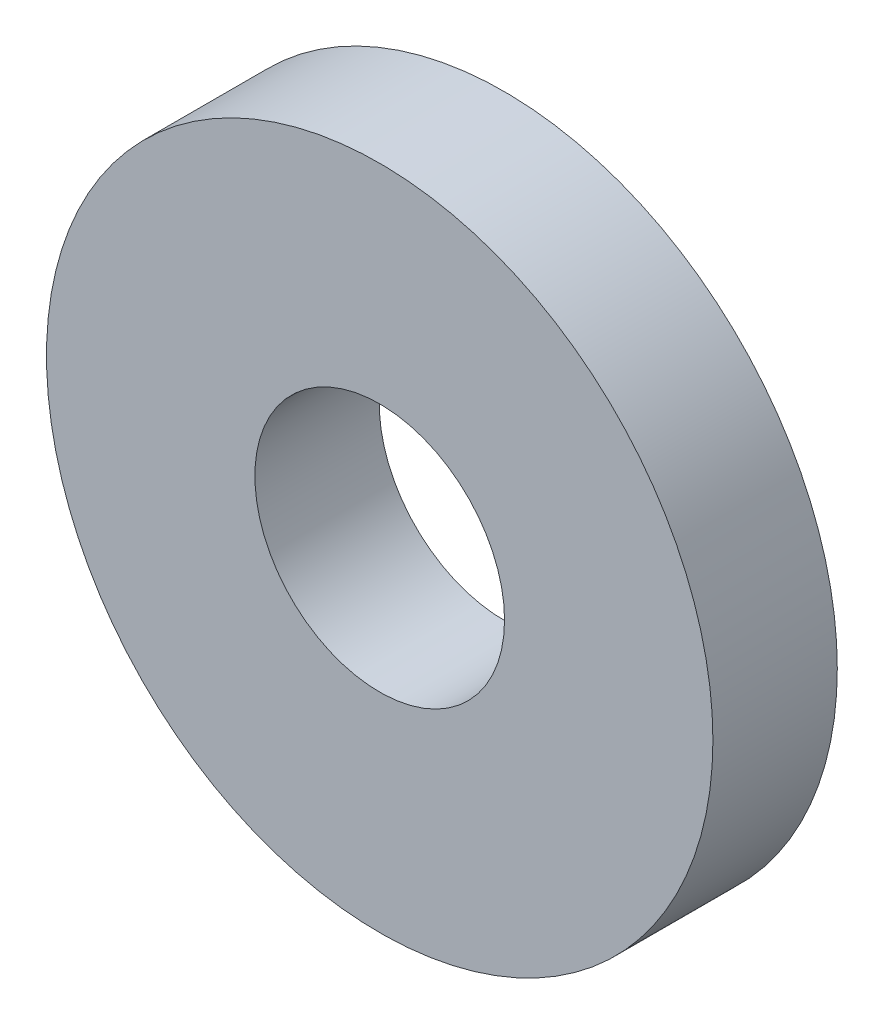
SolidWorks part; units mm, degrees
ref_plane "Front Plane" through (0, 0, 0) normal (0, 0, 1) x (1, 0, 0)
ref_plane "Top Plane" through (0, 0, 0) normal (0, 1, 0) x (1, 0, 0)
ref_plane "Right Plane" through (0, 0, 0) normal (1, 0, 0) x (0, 0, -1)
sketch "Sketch1" plane through (0, 0, 0) normal (1, 0, 0) x (0, 0, -1)
  line L0 (0, -3.5687) -> (0, 3.5687) construction
  line L1 (0, -9.525) -> (0, 9.525) construction
  line L2 (-1.778, 9.525) -> (1.778, 9.525)
  point P4 (0, 0)
  point P8 (0, 0)
  point P10 (0, 9.525)
  dimension "Thickness" = 3.556
sketch "Sketch2" plane through (0, 0, 0) normal (0, 0, 1) x (1, 0, 0)
  line L1 (0, -3.5687) -> (0, 3.5687) construction
  circle A2 centre (0, 0) radius 3.5687
  circle A3 centre (0, 0) radius 9.525
  point P3 (0, 0)
  dimension "D1" = 7.1374
  dimension "D2" = 19.05
extrude "Boss-Extrude1" add sketch "Sketch2" along normal mid plane 3.556
equation "\"D1@Boss-Extrude1\"=\"Thickness@Sketch1\""
equation "\"D1@Sketch2\"=\"ID@Sketch1\""
equation "\"D2@Sketch2\"=\"OD@Sketch1\""
